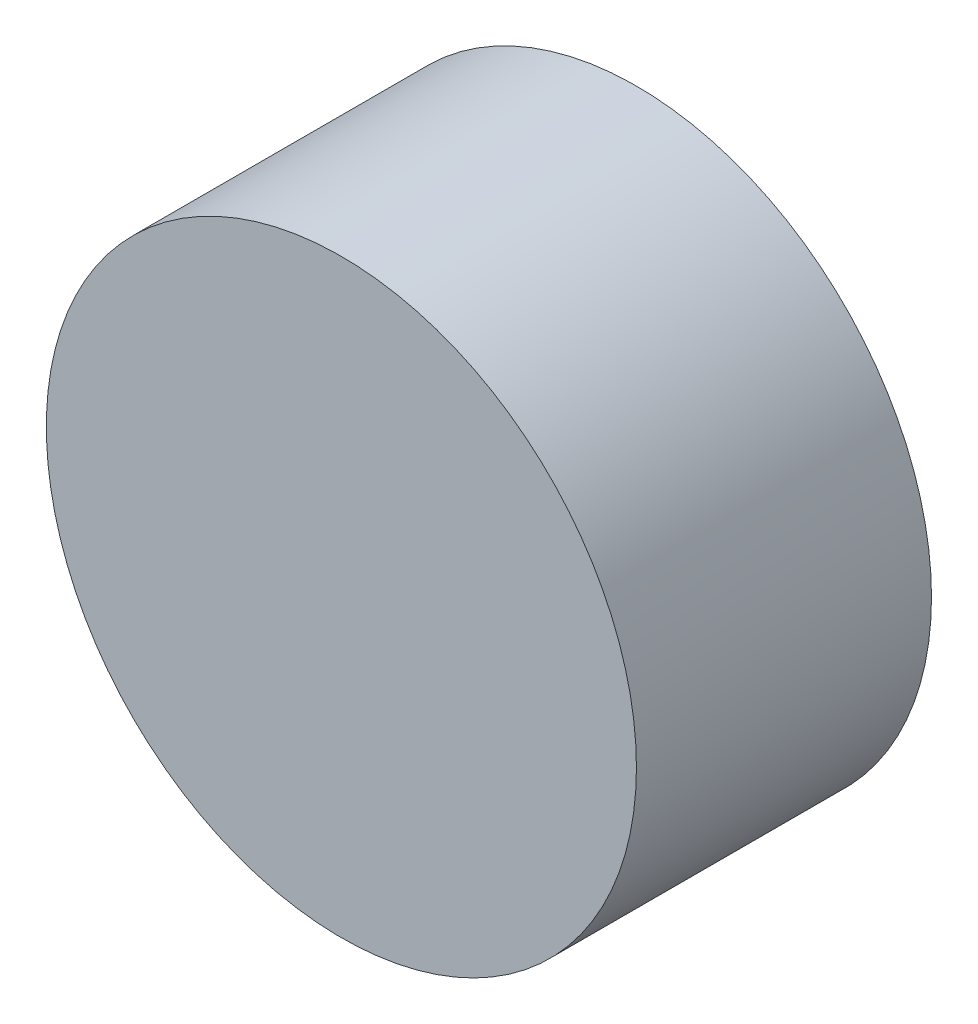
SolidWorks part; units mm, degrees
ref_plane "前视基准面" through (0, 0, 0) normal (0, 0, 1) x (1, 0, 0)
ref_plane "上视基准面" through (0, 0, 0) normal (0, 1, 0) x (1, 0, 0)
ref_plane "右视基准面" through (0, 0, 0) normal (1, 0, 0) x (0, 0, -1)
other "Configuration Table"
sketch "草图1" plane through (0, 0, 0) normal (0, 0, 1) x (1, 0, 0)
  circle A0 centre (0, 0) radius 5
  dimension "D1" = 10
extrude "凸台-拉伸1" add sketch "草图1" along normal blind 5
